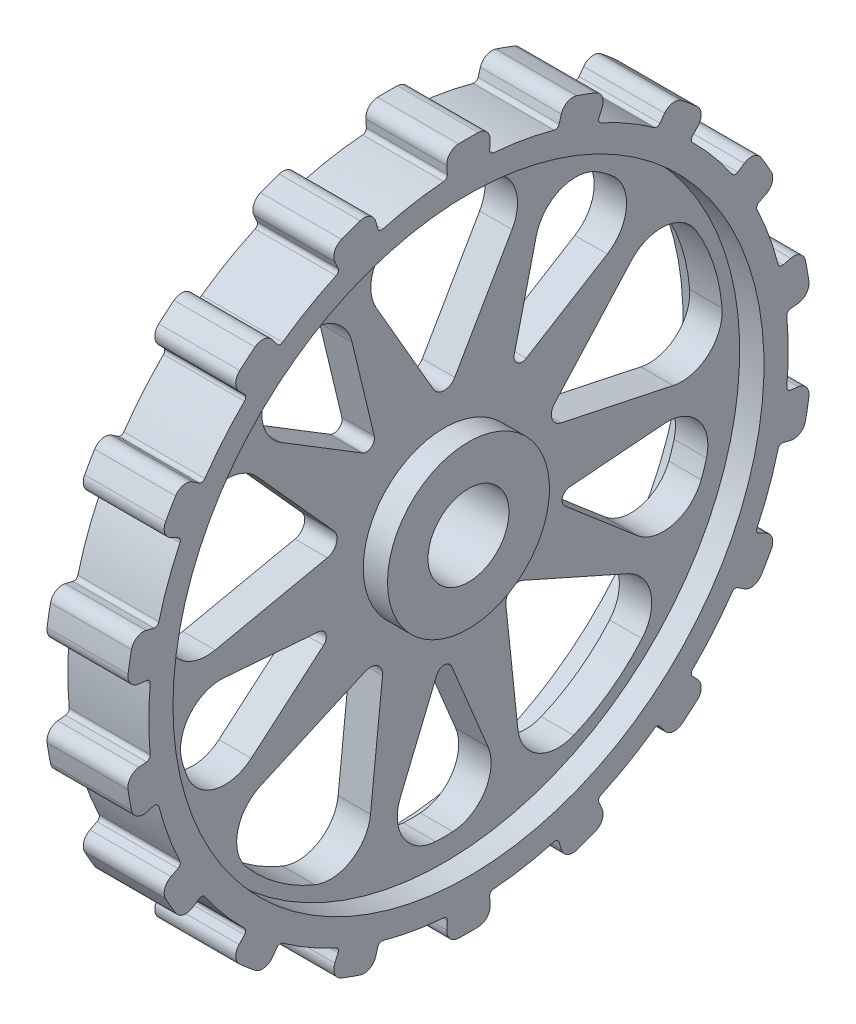
SolidWorks part; units mm, degrees
ref_plane "Спереди" through (0, 0, 0) normal (0, 0, 1) x (1, 0, 0)
ref_plane "Сверху" through (0, 0, 0) normal (0, 1, 0) x (1, 0, 0)
ref_plane "Справа" through (0, 0, 0) normal (1, 0, 0) x (0, 0, -1)
sketch "Эскиз1" plane through (0, 0, 0) normal (0, 0, 1) x (1, 0, 0)
  line L0 (6, -20) -> (6, -73)
  line L1 (0, -10) -> (20, -10)
  line L2 (0, -10) -> (0, -20)
  line L3 (0, -85) -> (20, -85)
  line L4 (20, -10) -> (20, -20)
  line L5 (14, -20) -> (14, -73)
  line L6 (0, 0) -> (20, 0) construction
  line L7 (10, -10) -> (10, -85) construction
  line L8 (0, -73) -> (0, -85)
  line L9 (0, -73) -> (6, -73)
  line L12 (6, -20) -> (0, -20)
  line L13 (14, -20) -> (20, -20)
  line L16 (20, -73) -> (14, -73)
  line L17 (20, -73) -> (20, -85)
  line L19 (20, -10) -> (20, -20)
  line L20 (20, -73) -> (20, -85)
  dimension "D1" = 20
  dimension "D2" = 75
  dimension "D3" = 10
  dimension "D4" = 10
  dimension "D5" = 6
  dimension "D6" = 12
  dimension "D7" = 0
revolve "Повернуть1" add sketch "Эскиз1" angle 360 about L6
sketch "Эскиз7" plane through (6, 0, 0) normal (-1, 0, 0) x (0, 0, 1)
  line L0 (0, 0) -> (0, 85) construction
  line L1 (-19.3, 58.5784) -> (-2.5894, 29.505)
  line L2 (2.6068, 29.495) -> (19.4298, 58.5035)
  line L5 (17.0462, 68.2684) -> (-2.3682, 68.3059) [skipped]
  arc A0 (-2.5894, 29.505) -> (2.6068, 29.495) centre (0.0116, 31) ccw
  circle A1 centre (0, 0) radius 85 construction
  arc A2 (-13.2876, 73.2021) -> (13.474, 73.1503) centre (0, 25) cw
  arc A3 (19.4298, 58.5035) -> (13.474, 73.1503) centre (10.7792, 63.5202) ccw
  arc A4 (-19.3, 58.5784) -> (-13.2876, 73.2021) centre (-10.6301, 63.5617) cw
  point P11 (0.0967, 74.9999)
  point P18 (0, 25)
  dimension "D3" = 50
  dimension "D4" = 10
  dimension "D6" = 3
  dimension "D1" = 25
  dimension "D2" = 50
  dimension "D5" = 19.3
sketch "Эскиз9" plane through (0, 0, 0) normal (0, 0, 1) x (1, 0, 0)
  line L0 (6, 0) -> (6, 85) construction
  line L1 (6, 70) -> (14, 70)
  line L2 (6, 70) -> (6, 25)
  line L3 (6, 25) -> (14, 25)
  line L4 (14, 70) -> (14, 25)
  line L5 (6, 75) -> (6, 73.1503) construction
  line L6 (14, -73) -> (14, 73) construction
  line L7 (6, 73) -> (6, -73) construction
  dimension "D1" = 45
  dimension "D2" = 25
revolve "Вырез-Повернуть9" cut sketch "Эскиз9" angle 60 mid plane about L3
fillet "Скругление1" radius 10 2 edges at (10, 63.9711, 22.5) (10, 63.9711, -22.5)
fillet "Скругление2" radius 3 1 edges at (10, 25, 0)
pattern_circular "Круговой массив3" count 5 over 360 about axis through (0, 0, 0) along (1, 0, 0) of "Вырез-Повернуть9", "Скругление1", "Скругление2"
sketch "Эскиз10" plane through (0, 0, 0) normal (0, 0, 1) x (1, 0, 0)
  line L0 (6, 73) -> (6, -73) construction
  line L1 (6, -27.5) -> (14, -27.5)
  line L2 (6, -27.5) -> (6, -67.5)
  line L3 (6, -67.5) -> (14, -67.5)
  line L4 (14, -27.5) -> (14, -67.5)
  line L5 (14, -73) -> (14, 73) construction
  dimension "D1" = 27.5
  dimension "D2" = 40
revolve "Вырез-Повернуть10" cut sketch "Эскиз10" angle 45 mid plane about L1
fillet "Скругление3" radius 10 2 edges at (10, -64.4552, 15.3073) (10, -64.4552, -15.3073)
fillet "Скругление4" radius 2 1 edges at (10, -27.5, 0)
pattern_circular "Круговой массив4" count 5 over 360 about axis through (0, 0, 0) along (1, 0, 0) of "Вырез-Повернуть10", "Скругление3", "Скругление4"
sketch "Эскиз12" plane through (0, 0, 0) normal (0, 1, 0) x (1, 0, 0)
  line L0 (6, -62.1868) -> (14, -62.1868) construction
  line L1 (0, -79) -> (0, -85)
  line L2 (0, -85) -> (20, -85)
  line L3 (20, -85) -> (20, -79)
  line L5 (0, -79) -> (20, -79)
  line L6 (0, 0) -> (20, 0) construction
  line L7 (0, 85) -> (0, -85) construction
  line L8 (20, -85) -> (20, 85) construction
  line L9 (0, -73) -> (20, -73) construction
  dimension "D1" = 6
revolve "Вырез-Повернуть15" cut sketch "Эскиз12" angle 12.5 mid plane about L6
fillet "Скругление5" radius 1 2 edges at (10, 8.6005, 78.5305) (10, -8.6005, 78.5305)
fillet "Скругление6" radius 3 2 edges at (10, 9.2537, 84.4948) (10, -9.2537, 84.4948)
pattern_circular "Круговой массив7" count 18 over 360 about axis through (0, 0, 0) along (1, 0, 0) of "Вырез-Повернуть15", "Скругление5", "Скругление6"
